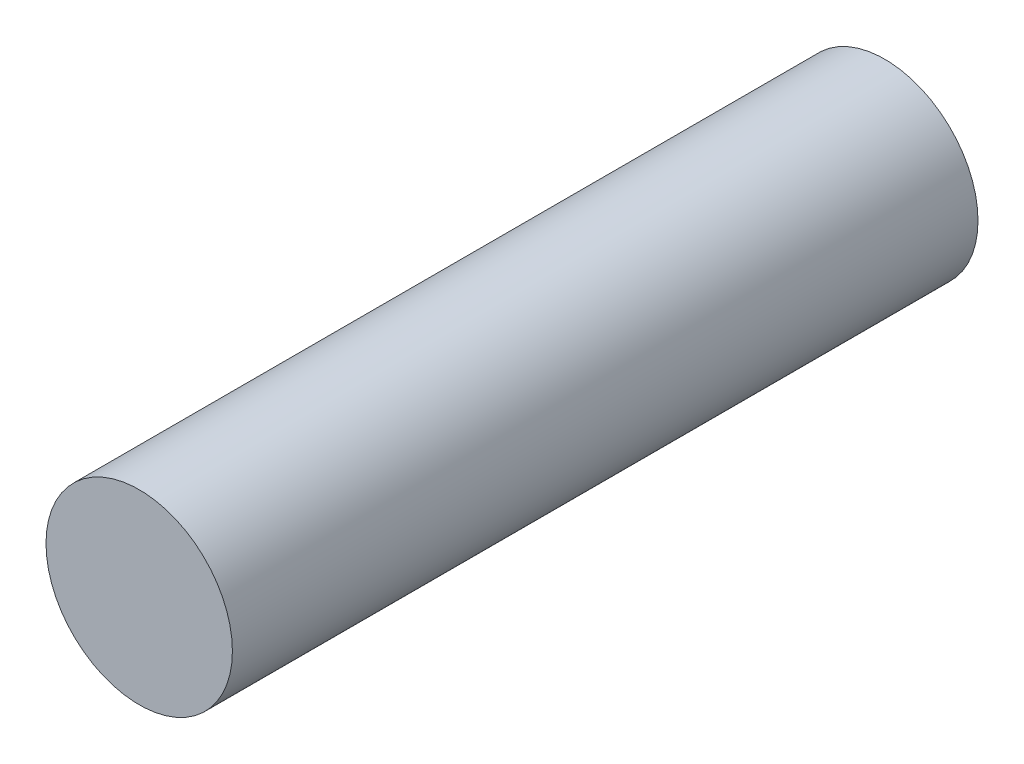
SolidWorks part; units mm, degrees
ref_plane "Front Plane" through (0, 0, 0) normal (0, 0, 1) x (1, 0, 0)
ref_plane "Top Plane" through (0, 0, 0) normal (0, 1, 0) x (1, 0, 0)
ref_plane "Right Plane" through (0, 0, 0) normal (1, 0, 0) x (0, 0, -1)
sketch "Sketch2" plane through (0, 0, 0) normal (0, 0, 1) x (1, 0, 0)
  circle A0 centre (0, 0) radius 3.175
  dimension "D1" = 6.35
extrude "Boss-Extrude1" add sketch "Sketch2" along normal blind 25.4
